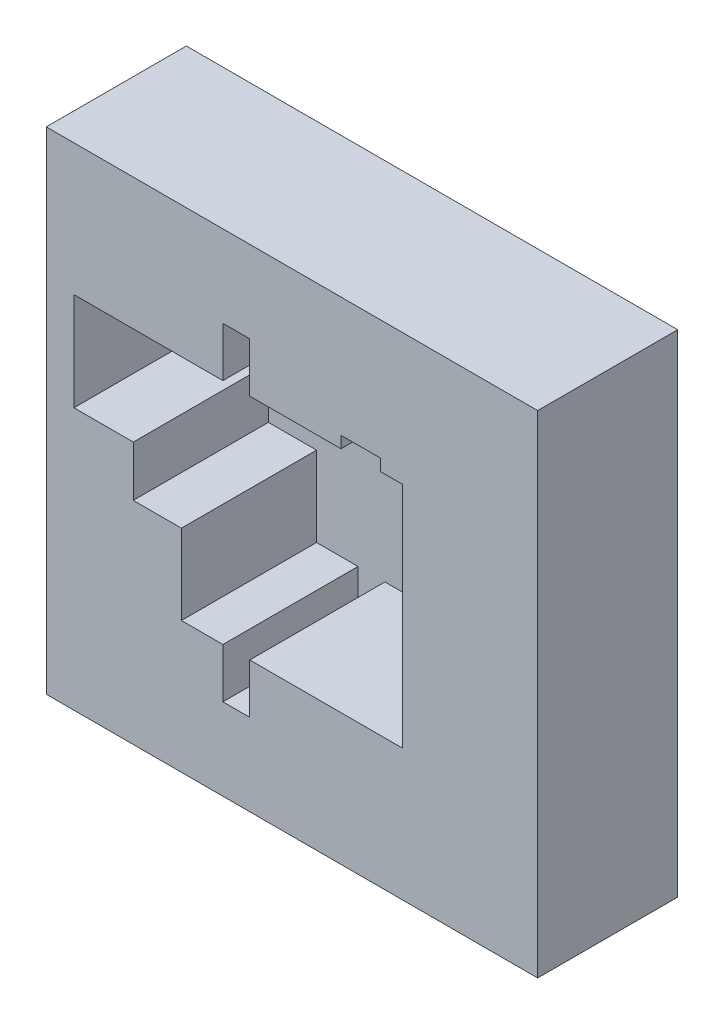
SolidWorks part; units mm, degrees
ref_plane "Front Plane" through (0, 0, 0) normal (0, 0, 1) x (1, 0, 0)
ref_plane "Top Plane" through (0, 0, 0) normal (0, 1, 0) x (1, 0, 0)
ref_plane "Right Plane" through (0, 0, 0) normal (1, 0, 0) x (0, 0, -1)
sketch "Sketch1" plane through (0, 0, 0) normal (0, 0, 1) x (1, 0, 0)
  line L1 (-48.3282, 53.2718) -> (2.4718, 53.2718)
  line L2 (-48.3282, 53.2718) -> (-48.3282, 2.4718)
  line L3 (-48.3282, 2.4718) -> (2.4718, 2.4718)
  line L4 (2.4718, 53.2718) -> (2.4718, 2.4718)
  dimension "D1" = 50.8
  dimension "D2" = 50.8
extrude "Boss-Extrude1" add sketch "Sketch1" along normal blind 14.478
sketch "Sketch3" plane through (0, 0, 14.478) normal (0, 0, 1) x (1, 0, 0)
  line L0 (-22.9282, 53.2718) -> (-22.9282, 2.4718)
  line L1 (2.4718, 53.2718) -> (-48.3282, 53.2718) construction
  line L2 (-48.3282, 2.4718) -> (2.4718, 2.4718) construction
  line L3 (-48.3282, 27.8718) -> (2.4718, 27.8718)
  line L4 (-48.3282, 53.2718) -> (-48.3282, 2.4718) construction
  line L5 (2.4718, 2.4718) -> (2.4718, 53.2718) construction
  line L6 (-34.3582, 39.6828) -> (-30.0685, 39.6828)
  line L7 (-34.3582, 39.6828) -> (-11.4982, 39.6828)
  line L8 (-34.3582, 39.6828) -> (-34.3582, 16.0608)
  line L9 (-34.3582, 16.0608) -> (-11.4982, 16.0608)
  line L10 (-11.4982, 39.6828) -> (-11.4982, 16.0608)
  line L11 (-34.3582, 39.6828) -> (-11.4982, 16.0608) construction
  line L12 (-34.3582, 16.0608) -> (-11.4982, 39.6828) construction
  line L13 (-30.0685, 39.6828) -> (-30.0685, 44.812)
  line L14 (-30.0685, 44.812) -> (-27.2934, 44.812)
  line L15 (-27.2934, 44.812) -> (-27.2934, 39.6828)
  line L16 (-30.0685, 39.6828) -> (-27.2934, 39.6828)
  line L17 (-34.3582, 16.0608) -> (-30.0685, 16.0608)
  line L18 (-30.0685, 16.0608) -> (-30.0685, 10.928)
  line L19 (-30.0685, 10.928) -> (-27.2934, 10.928)
  line L20 (-27.2934, 10.928) -> (-27.2934, 16.0608)
  line L21 (-34.3582, 39.6828) -> (-34.3582, 24.3293)
  line L22 (-34.3582, 24.3293) -> (-39.3328, 24.3293)
  line L23 (-39.3328, 24.3293) -> (-39.3328, 39.6828)
  line L24 (-39.3328, 39.6828) -> (-34.3582, 39.6828)
  line L25 (-39.3328, 39.6828) -> (-34.3582, 39.6828)
  line L26 (-39.3328, 39.6828) -> (-39.3328, 29.5515)
  line L27 (-39.3328, 29.5515) -> (-45.4669, 29.5515)
  line L28 (-45.4669, 29.5515) -> (-45.4669, 39.6828)
  line L29 (-45.4669, 39.6828) -> (-39.3328, 39.6828)
  line L30 (-11.4982, 39.6828) -> (-17.8687, 39.6828)
  line L31 (-17.8687, 39.6828) -> (-17.8687, 40.8904)
  line L32 (-17.8687, 40.8904) -> (-13.7717, 40.8904)
  line L33 (-13.7717, 40.8904) -> (-13.7717, 39.6828)
  point P12 (-22.9282, 27.8718)
  dimension "D1" = 22.86
  dimension "D2" = 23.622
extrude "Cut-Extrude1" cut sketch "Sketch3" against normal blind 13.97 contours L29 L28 L27 L23 | L24 L23 L3 L8 | L6 L8 L3 L0 L7 | L10 L30 L7 L0 L3 | L8 L9 L0 L3 | L23 L22 L8 L3 | L19 L20 L9 L18 | L15 L14 L13 L7 | L10 L3 L0 L9 | L33 L32 L31 L7
